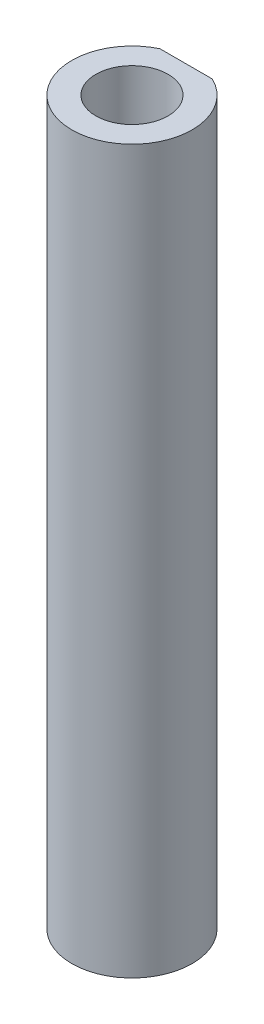
SolidWorks part; units mm, degrees
ref_plane "Front Plane" through (0, 0, 0) normal (0, 0, 1) x (1, 0, 0)
ref_plane "Top Plane" through (0, 0, 0) normal (0, 1, 0) x (1, 0, 0)
ref_plane "Right Plane" through (0, 0, 0) normal (1, 0, 0) x (0, 0, -1)
sketch "Sketch4" plane through (0, 0, 0) normal (0, 1, 0) x (1, 0, 0)
  circle A0 centre (0, 0) radius 3
  circle A1 centre (0, 0) radius 5
  dimension "D1" = 6
  dimension "D2" = 10
extrude "Boss-Extrude1" add sketch "Sketch4" along normal mid plane 60
sketch "Sketch6" plane through (0, 0, 0) normal (0, 1, 0) x (1, 0, 0)
  line L0 (0, 0) -> (0, 5.9157) construction
  line L1 (0, 0) -> (6.342, 0) construction
sketch "Sketch10" plane through (0, 30, 0) normal (0, 1, 0) x (1, 0, 0)
  line L0 (2.1794, 4.5) -> (-2.1794, 4.5)
  circle A0 centre (0, 0) radius 5 construction
  arc A1 (2.1794, 4.5) -> (-2.1794, 4.5) centre (0, 0) ccw
  dimension "D1" = 4.5
extrude "Cut-Extrude1" cut sketch "Sketch10" against normal blind 10
mirror "Mirror2" about plane through (0, 0, 0) normal (0, 1, 0) of "Cut-Extrude1"
